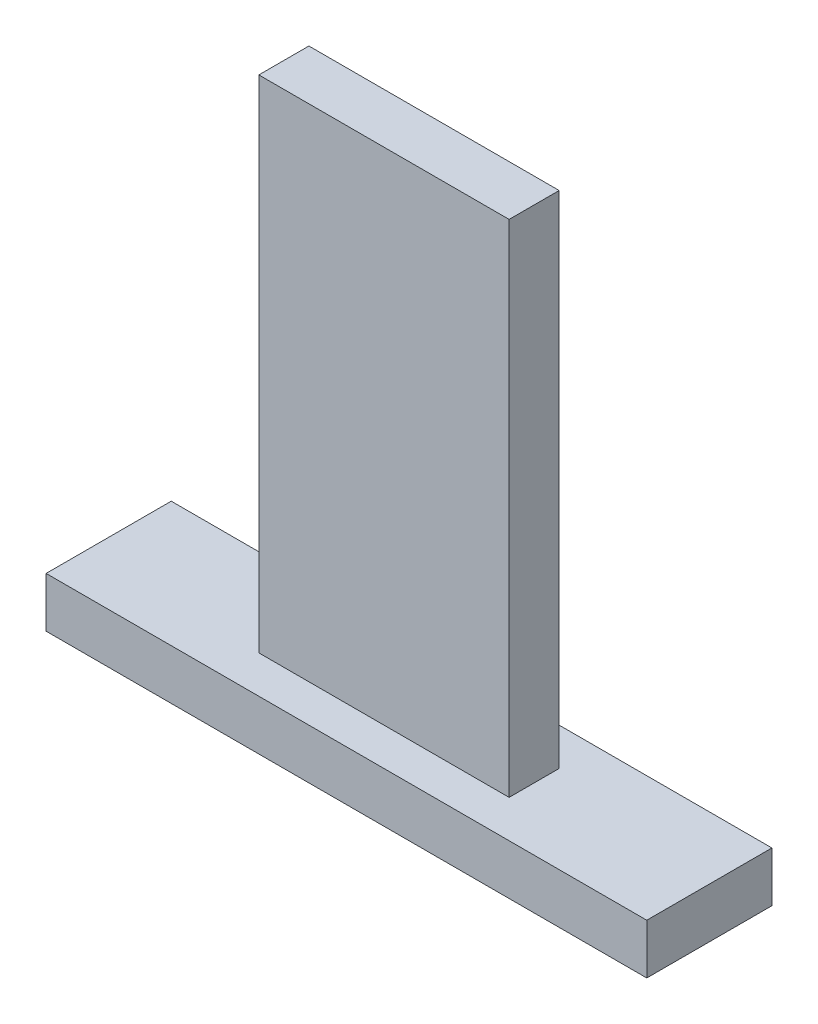
SolidWorks part; units mm, degrees
ref_plane "前视基准面" through (0, 0, 0) normal (0, 0, 1) x (1, 0, 0)
ref_plane "上视基准面" through (0, 0, 0) normal (0, 1, 0) x (1, 0, 0)
ref_plane "右视基准面" through (0, 0, 0) normal (1, 0, 0) x (0, 0, -1)
sketch "草图1" plane through (0, 0, 0) normal (0, 0, 1) x (1, 0, 0)
  line L0 (-1041.6234, 0) -> (783.7962, 0) construction
  line L1 (-500, 1000) -> (500, 1000)
  line L2 (-500, 1000) -> (-500, -1000)
  line L3 (-500, -1000) -> (500, -1000)
  line L4 (500, 1000) -> (500, -1000)
  line L5 (0, 1591.9641) -> (0, -1423.5968) construction
  dimension "D1" = 1000
  dimension "D2" = 2000
extrude "凸台-拉伸1" add sketch "草图1" along normal blind 200
sketch "草图2" plane through (0, -1000, 0) normal (0, -1, 0) x (1, 0, 0)
  line L0 (-987.2692, 100) -> (1059.4284, 100) construction
  line L1 (-1200, 350) -> (1200, 350)
  line L2 (-1200, 350) -> (-1200, -150)
  line L3 (-1200, -150) -> (1200, -150)
  line L4 (1200, 350) -> (1200, -150)
  line L5 (-500, 200) -> (500, 200) construction
  line L6 (-500, 0) -> (500, 0) construction
  line L7 (0, 551.5417) -> (0, -533.0331) construction
  dimension "D1" = 500
  dimension "D2" = 2400
extrude "凸台-拉伸2" add sketch "草图2" along normal blind 200
